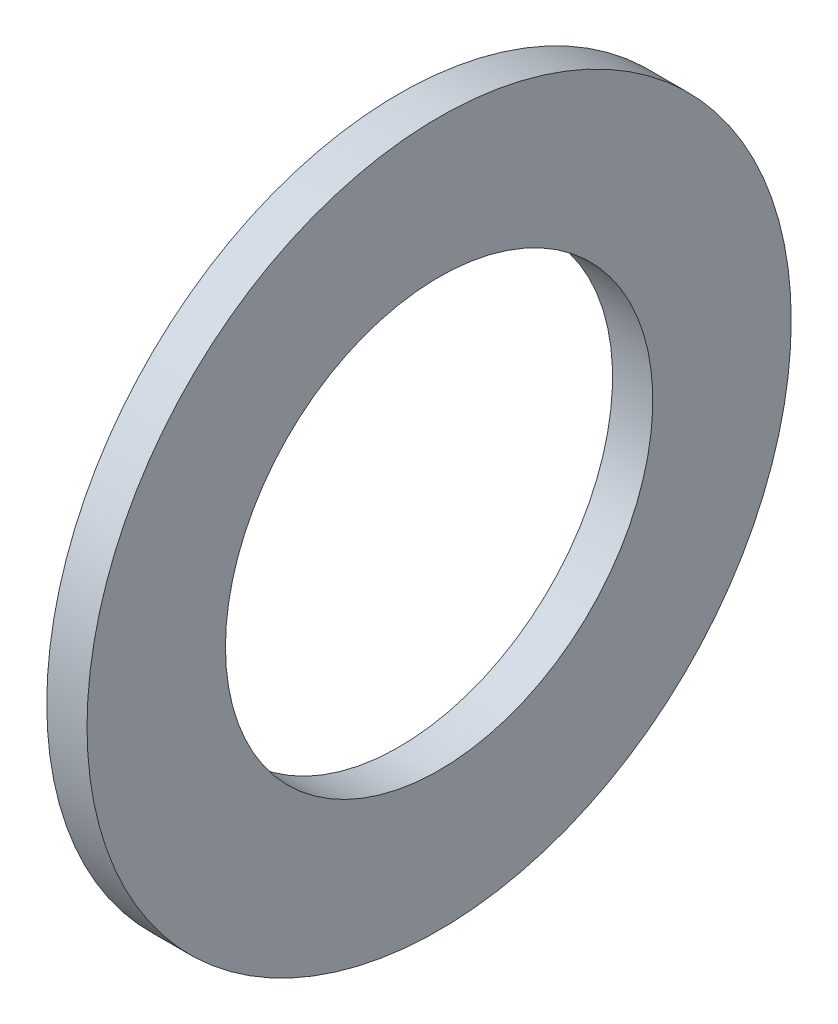
SolidWorks part; units mm, degrees
ref_plane "Plane1" through (0, 0, 0) normal (0, 0, 1) x (1, 0, 0)
ref_plane "Plane2" through (0, 0, 0) normal (0, 1, 0) x (1, 0, 0)
ref_plane "Plane3" through (0, 0, 0) normal (1, 0, 0) x (0, 0, -1)
sketch "Sketch1" plane through (0, 0, 0) normal (0, 0, 1) x (1, 0, 0)
  line L0 (-34.925, 0) -> (9.525, 0) construction
  line L1 (0, 13.4874) -> (0, 22.225)
  line L2 (0, 22.225) -> (-2.54, 22.225)
  line L3 (-2.54, 22.225) -> (-2.54, 13.4874)
  line L4 (-2.54, 13.4874) -> (0, 13.4874)
  dimension "Thickness" = 2.54
  dimension "Inside_dia" = 26.9748
  dimension "Outside_dia" = 44.45
revolve "Base-Revolve" add sketch "Sketch1" angle 360 about L0
